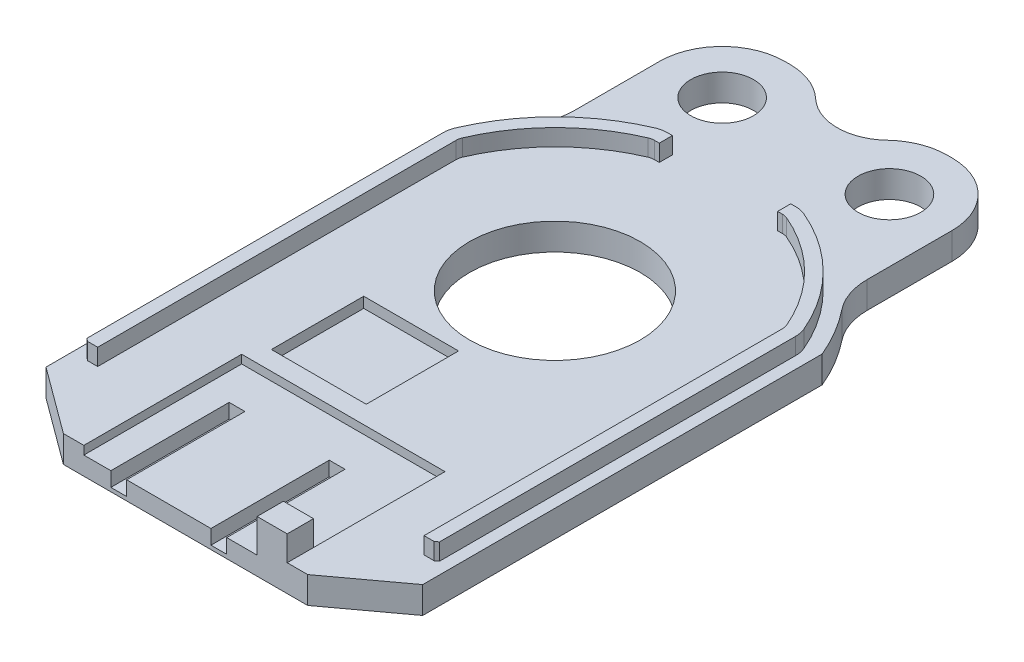
SolidWorks part; units mm, degrees
ref_plane "Front Plane" through (0, 0, 0) normal (0, 0, 1) x (1, 0, 0)
ref_plane "Top Plane" through (0, 0, 0) normal (0, 1, 0) x (1, 0, 0)
ref_plane "Right Plane" through (0, 0, 0) normal (1, 0, 0) x (0, 0, -1)
sketch "Sketch1" plane through (0, 0, 0) normal (0, 1, 0) x (1, 0, 0)
  line L0 (-14.3002, 5.9944) -> (-14.3002, -24.3332)
  line L1 (-14.3002, -24.3332) -> (-9.271, -28.0416)
  line L2 (-9.271, -28.0416) -> (9.271, -28.0416)
  line L3 (9.271, -28.0416) -> (14.3002, -24.3332)
  line L4 (14.3002, -24.3332) -> (14.3002, 5.9944)
  circle A0 centre (0, 0) radius 6.477
  arc A1 (-14.3002, 5.9944) -> (14.3002, 5.9944) centre (0, 0) cw
  dimension "D1" = 12.954
  dimension "D2" = 14.3002
  dimension "D3" = 14.3002
  dimension "D4" = 28.0416
  dimension "D5" = 5.0292
  dimension "D6" = 3.7084
  dimension "D7" = 3.7084
  dimension "D8" = 5.0292
  dimension "D9" = 34.036
extrude "Boss-Extrude1" add sketch "Sketch1" along normal blind 2.032
sketch "Sketch2" plane through (0, 2.032, 0) normal (0, 1, 0) x (1, 0, 0)
  line L0 (0, -28.0416) -> (-7.7191, -28.0416)
  line L1 (-9.271, -28.0416) -> (9.271, -28.0416) construction
  line L2 (0, -28.0416) -> (7.7191, -28.0416)
  line L3 (-7.7191, -28.0416) -> (-7.7191, -16.0604)
  line L4 (-7.7191, -16.0604) -> (7.7191, -16.0604)
  line L5 (7.7191, -16.0604) -> (7.7191, -28.0416)
  dimension "D1" = 7.7191
  dimension "D2" = 7.7191
  dimension "D3" = 11.9812
extrude "Cut-Extrude1" cut sketch "Sketch2" against normal blind 0.6401
sketch "Sketch3" plane through (0, 1.3919, 0) normal (0, 1, 0) x (1, 0, 0)
  line L0 (-7.7191, -28.0416) -> (7.7191, -28.0416) construction
  line L1 (-5.6693, -28.0416) -> (-4.4704, -28.0416)
  line L2 (-5.6693, -28.0416) -> (-5.6693, -19.0602)
  line L3 (-5.6693, -19.0602) -> (-4.4704, -19.0602)
  line L4 (-4.4704, -28.0416) -> (-4.4704, -19.0602)
  line L5 (-7.7191, -16.0604) -> (-7.7191, -28.0416) construction
  line L6 (1.9304, -28.0416) -> (3.1293, -28.0416)
  line L7 (1.9304, -28.0416) -> (1.9304, -19.0602)
  line L8 (1.9304, -19.0602) -> (3.1293, -19.0602)
  line L9 (3.1293, -28.0416) -> (3.1293, -19.0602)
  dimension "D1" = 2.0498
  dimension "D2" = 1.1989
  dimension "D3" = 6.4008
  dimension "D4" = 1.1989
  dimension "D5" = 8.9814
  dimension "D6" = 8.9814
extrude "Cut-Extrude2" cut sketch "Sketch3" against normal blind 1.0998
sketch "Sketch4" plane through (0, 2.032, 0) normal (0, 1, 0) x (1, 0, 0)
  line L0 (-7.7191, -16.0604) -> (-7.7191, -28.0416) construction
  line L1 (-6.8991, -14.6205) -> (0.2992, -14.6205)
  line L2 (-6.8991, -14.6205) -> (-6.8991, -7.6126)
  line L3 (-6.8991, -7.6126) -> (0.2992, -7.6126)
  line L4 (0.2992, -14.6205) -> (0.2992, -7.6126)
  line L5 (7.7191, -16.0604) -> (-7.7191, -16.0604) construction
  dimension "D1" = 0.8199
  dimension "D2" = 1.4399
  dimension "D3" = 7.0079
  dimension "D4" = 7.1984
extrude "Cut-Extrude3" cut sketch "Sketch4" against normal blind 0.8001
sketch "Sketch5" plane through (0, 2.032, 0) normal (0, 1, 0) x (1, 0, 0)
  line L0 (12.4028, -22.3342) -> (13.1717, -22.3342)
  line L1 (13.1717, -22.3342) -> (13.401, -22.1529)
  line L2 (13.401, -22.1529) -> (13.401, 4.8829)
  line L3 (12.4028, -22.3342) -> (12.4028, 4.8819)
  line L4 (7.7191, -28.0416) -> (9.271, -28.0416) construction
  line L5 (14.3002, -24.3332) -> (14.3002, 5.9944) construction
  line L6 (4.8793, 13.401) -> (4.5034, 13.401)
  line L7 (4.5034, 13.401) -> (4.5034, 12.4028)
  line L8 (4.5034, 12.4028) -> (4.8793, 12.4028)
  line L9 (0.0143, 14.8202) -> (0.0143, -25.5245) construction
  line L10 (-4.8508, 13.401) -> (-4.4748, 13.401)
  line L11 (-4.4748, 13.401) -> (-4.4748, 12.4028)
  line L12 (-4.4748, 12.4028) -> (-4.8508, 12.4028)
  line L13 (-12.3742, -22.3342) -> (-12.3742, 4.8819)
  line L14 (-12.3742, -22.3342) -> (-13.1431, -22.3342)
  line L15 (-13.1431, -22.3342) -> (-13.3725, -22.1529)
  line L16 (-13.3725, -22.1529) -> (-13.3725, 4.8829)
  arc A0 (5.2725, 12.3222) -> (12.3222, 5.2751) centre (0.0143, 0.0124) cw
  arc A1 (4.8793, 12.4028) -> (5.2725, 12.3222) centre (4.8793, 11.404) cw
  arc A2 (12.4028, 4.8819) -> (12.3222, 5.2751) centre (11.404, 4.8819) ccw
  arc A3 (5.6081, 13.2644) -> (13.2397, 5.6678) centre (0.0024, 0.0011) cw
  arc A4 (4.8793, 13.401) -> (5.6081, 13.2644) centre (4.8793, 11.3897) cw
  arc A5 (13.2397, 5.6678) -> (13.401, 4.8829) centre (11.4022, 4.8811) cw
  arc A6 (-5.5795, 13.2644) -> (-13.2112, 5.6678) centre (0.0262, 0.0011) ccw
  arc A7 (-4.8508, 13.401) -> (-5.5795, 13.2644) centre (-4.8508, 11.3897) ccw
  arc A8 (-4.8508, 12.4028) -> (-5.2439, 12.3222) centre (-4.8508, 11.404) ccw
  arc A9 (-5.2439, 12.3222) -> (-12.2936, 5.2751) centre (0.0143, 0.0124) ccw
  arc A10 (-12.3742, 4.8819) -> (-12.2936, 5.2751) centre (-11.3754, 4.8819) cw
  arc A11 (-13.2112, 5.6678) -> (-13.3725, 4.8829) centre (-11.3736, 4.8811) ccw
  dimension "D17" = 13.3858
  dimension "D22" = 14.3993
  dimension "D1" = 5.7074
  dimension "D2" = 0.2294
  dimension "D3" = 0.1814
  dimension "D4" = 0.8992
  dimension "D5" = 0.9982
  dimension "D6" = 27.2161
  dimension "D7" = 27.0358
  dimension "D8" = 7.8994
  dimension "D9" = 7.5209
  dimension "D10" = 0.9982
  dimension "D11" = 0.3759
  dimension "D12" = 0.3759
  dimension "D13" = 0.3932
  dimension "D14" = 0.0806
  dimension "D15" = 0.3932
  dimension "D16" = 0.0806
  dimension "D18" = 0.7287
  dimension "D19" = 0.1367
  dimension "D20" = 0.1613
  dimension "D21" = 0.7849
extrude "Boss-Extrude2" add sketch "Sketch5" along normal blind 1.27
sketch "Sketch6" plane through (0, 1.3919, 0) normal (0, 1, 0) x (1, 0, 0)
  line L1 (7.7191, -28.0416) -> (5.4331, -28.0416)
  line L2 (7.7191, -28.0416) -> (7.7191, -26.0426)
  line L3 (7.7191, -26.0426) -> (5.4331, -26.0426)
  line L4 (5.4331, -28.0416) -> (5.4331, -26.0426)
  dimension "D1" = 2.286
  dimension "D2" = 1.999
extrude "Boss-Extrude3" add sketch "Sketch6" along normal blind 2.54
sketch "Sketch7" plane through (0, 0, 0) normal (0, -1, 0) x (1, 0, 0)
  line L0 (-11.1125, -12.6011) -> (-11.1125, -19.05)
  line L1 (-6.35, -23.8125) -> (-5.9834, -23.8125)
  line L2 (11.1125, -19.05) -> (11.1125, -12.6011)
  line L3 (6.35, -23.8125) -> (5.9834, -23.8125)
  circle A0 centre (6.35, -19.05) radius 2.3813
  circle A1 centre (-6.35, -19.05) radius 2.3813
  arc A2 (-14.3002, -5.9944) -> (14.3002, -5.9944) centre (0, 0) ccw construction
  arc A3 (11.1125, -19.05) -> (6.35, -23.8125) centre (6.35, -19.05) cw
  arc A4 (-11.1125, -19.05) -> (-6.35, -23.8125) centre (-6.35, -19.05) ccw
  arc A6 (-2.7174, -22.5162) -> (-5.9834, -23.8125) centre (-5.9834, -19.05) cw
  arc A7 (-2.7174, -22.5162) -> (2.7174, -22.5162) centre (0, -25.4) cw
  arc A8 (2.7174, -22.5162) -> (5.9834, -23.8125) centre (5.9834, -19.05) ccw
  arc A9 (-12.1448, -9.6401) -> (-14.3002, -5.9944) centre (0, 0) cw
  arc A10 (-12.1448, -9.6401) -> (-11.1125, -12.6011) centre (-15.875, -12.6011) cw
  arc A11 (12.1448, -9.6401) -> (14.3002, -5.9944) centre (0, 0) ccw
  arc A12 (11.1125, -12.6011) -> (12.1448, -9.6401) centre (15.875, -12.6011) cw
  point P23 (3.6305, -23.8125)
  point P29 (-11.1125, -10.8139)
  point P35 (11.1125, -10.8139)
  arc M5 (-14.3002, -5.9944) -> (14.3002, -5.9944) centre (0, 0) ccw
  dimension "D5" = 4.7625
  dimension "D6" = 4.7625
  dimension "D10" = 4.7625
  dimension "D12" = 4.7625
  dimension "D13" = 4.7625
  dimension "D14" = 4.7625
  dimension "D15" = 4.7625
  dimension "D1" = 19.05
  dimension "D2" = 19.05
  dimension "D3" = 6.35
  dimension "D4" = 6.35
  dimension "D7" = 4.7625
  dimension "D8" = 4.7625
  dimension "D9" = 4.7625
  dimension "D11" = 25.4
extrude "Boss-Extrude4" add sketch "Sketch7" against normal blind 2.032 contours L0 A4 L1 A3 L2 A0 A1 M5
